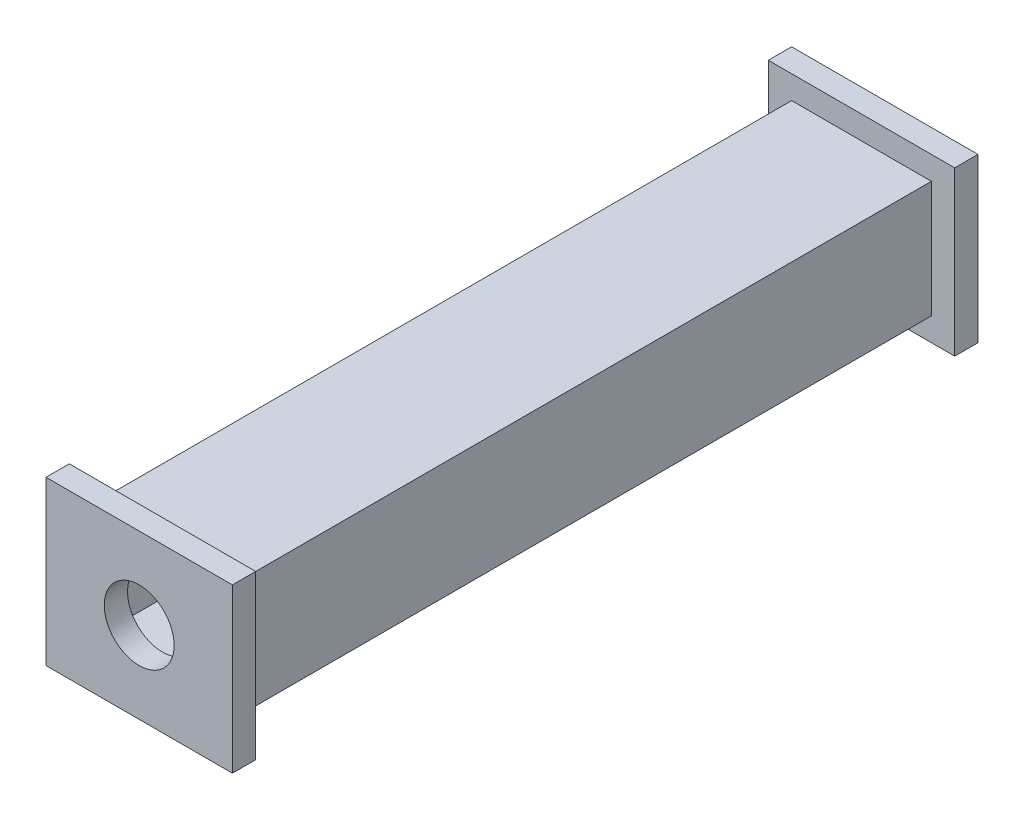
SolidWorks part; units mm, degrees
ref_plane "前视基准面" through (0, 0, 0) normal (0, 0, 1) x (1, 0, 0)
ref_plane "上视基准面" through (0, 0, 0) normal (0, 1, 0) x (1, 0, 0)
ref_plane "右视基准面" through (0, 0, 0) normal (1, 0, 0) x (0, 0, -1)
other "Configuration Table"
sketch "草图8" plane through (0, 0, 0) normal (0, 0, 1) x (1, 0, 0)
  line L1 (-30, 25) -> (30, 25)
  line L2 (-30, 25) -> (-30, -25)
  line L3 (-30, -25) -> (30, -25)
  line L4 (30, 25) -> (30, -25)
  line L5 (-25, 20) -> (25, 20)
  line L6 (-25, 20) -> (-25, -20)
  line L7 (-25, -20) -> (25, -20)
  line L8 (25, 20) -> (25, -20)
extrude "凸台-拉伸1" add sketch "草图8" along normal mid plane 300
sketch "草图9" plane through (0, 0, 150) normal (0, 0, 1) x (1, 0, 0)
  line L1 (-40, 35) -> (40, 35)
  line L2 (-40, 35) -> (-40, -35)
  line L3 (-40, -35) -> (40, -35)
  line L4 (40, 35) -> (40, -35)
  circle A0 centre (0, 0) radius 15
extrude "凸台-拉伸2" add sketch "草图9" along normal blind 10
sketch "草图10" plane through (0, 0, -150) normal (0, 0, -1) x (-1, 0, 0)
  line L1 (-40, 35) -> (40, 35)
  line L2 (-40, 35) -> (-40, -35)
  line L3 (-40, -35) -> (40, -35)
  line L4 (40, 35) -> (40, -35)
  circle A0 centre (0, 0) radius 15
extrude "凸台-拉伸3" add sketch "草图10" along normal blind 10
